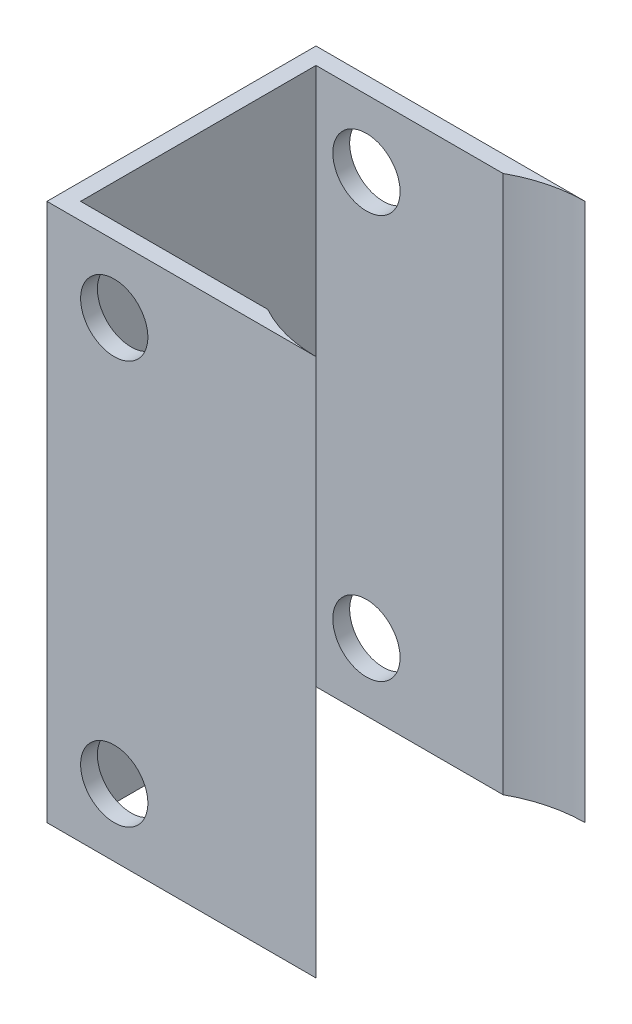
SolidWorks part; units mm, degrees
ref_plane "Front Plane" through (0, 0, 0) normal (0, 0, 1) x (1, 0, 0)
ref_plane "Top Plane" through (0, 0, 0) normal (0, 1, 0) x (1, 0, 0)
ref_plane "Right Plane" through (0, 0, 0) normal (1, 0, 0) x (0, 0, -1)
sketch "Sketch1" plane through (0, 0, 0) normal (0, 1, 0) x (1, 0, 0)
  line L1 (-12.7, 12.7) -> (12.7, 12.7)
  line L2 (-12.7, 12.7) -> (-12.7, -12.7)
  line L3 (-12.7, -12.7) -> (12.7, -12.7)
  line L4 (12.7, 12.7) -> (12.7, -12.7)
  line L5 (-12.7, 12.7) -> (12.7, -12.7) construction
  line L6 (-12.7, -12.7) -> (12.7, 12.7) construction
  line L7 (-11.1125, 11.1125) -> (11.1125, 11.1125)
  line L8 (-11.1125, 11.1125) -> (-11.1125, -11.1125)
  line L9 (-11.1125, -11.1125) -> (11.1125, -11.1125)
  line L10 (11.1125, 11.1125) -> (11.1125, -11.1125)
  line L11 (-11.1125, 11.1125) -> (11.1125, -11.1125) construction
  line L12 (-11.1125, -11.1125) -> (11.1125, 11.1125) construction
  point P0 (0, 0)
  point P6 (0, 0)
  dimension "D1" = 25.4
  dimension "D2" = 1.5875
extrude "Boss-Extrude1" add sketch "Sketch1" along normal blind 50.8
sketch "Sketch2" plane through (0, 50.8, 0) normal (0, 1, 0) x (1, 0, 0)
  line L10 (-12.7, 12.7) -> (-12.7, -12.7) construction
  circle A2 centre (12.7, 0) radius 12.7
  dimension "D1" = 25.4
extrude "Cut-Extrude1" cut sketch "Sketch2" against normal through all
sketch "Sketch3" plane through (0, 0, -12.7) normal (0, 0, -1) x (-1, 0, 0)
  line L1 (-12.7, 50.8) -> (12.7, 50.8) construction
  line L3 (12.7, 50.8) -> (12.7, 0) construction
  circle A0 centre (6.35, 44.45) radius 3.175
  circle A1 centre (6.35, 6.35) radius 3.175
  point P6 (-8.3267, 44.046)
  point P9 (0, 0)
  dimension "D1" = 38.1
  dimension "D2" = 6.35
  dimension "D3" = 6.35
extrude "Cut-Extrude2" cut sketch "Sketch3" against normal through all
